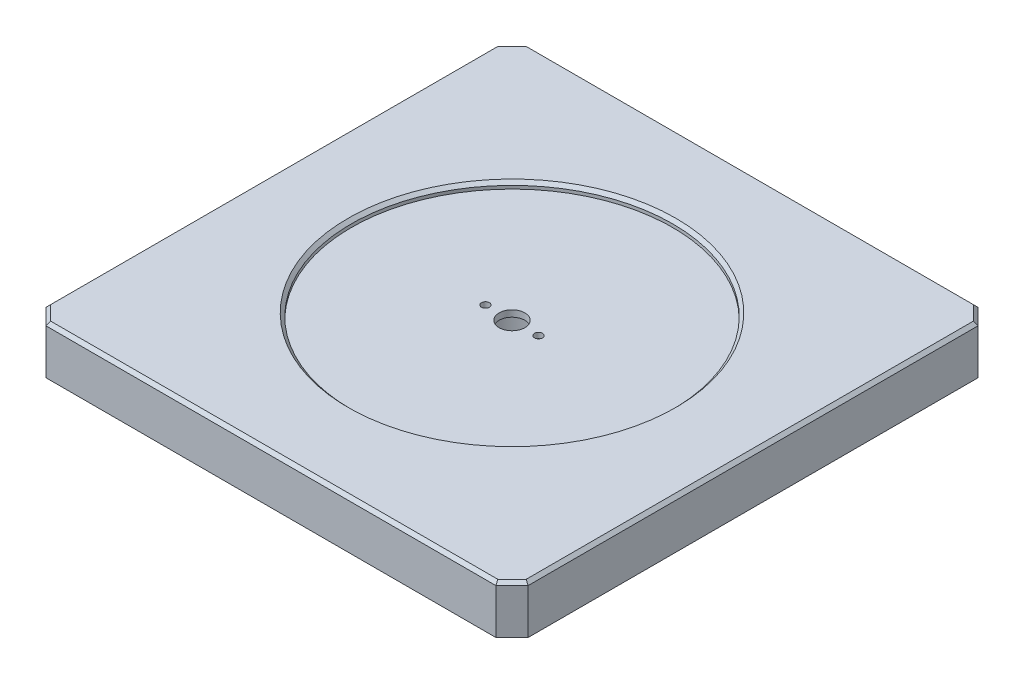
SolidWorks part; units mm, degrees
material "Plain Carbon Steel"
ref_plane "Front Plane" through (0, 0, 0) normal (0, 0, 1) x (1, 0, 0)
ref_plane "Top Plane" through (0, 0, 0) normal (0, 1, 0) x (1, 0, 0)
ref_plane "Right Plane" through (0, 0, 0) normal (1, 0, 0) x (0, 0, -1)
sketch "Sketch1" plane through (0, 0, 0) normal (0, 1, 0) x (1, 0, 0)
  line L1 (75, 75) -> (-75, 75)
  line L2 (75, 75) -> (75, -75)
  line L3 (75, -75) -> (-75, -75)
  line L4 (-75, 75) -> (-75, -75)
  dimension "D1" = 150
  dimension "D2" = 150
  dimension "D3" = 75
  dimension "D4" = 75
extrude "Boss-Extrude1" add sketch "Sketch1" along normal blind 15
sketch "Sketch2" plane through (0, 0, 0) normal (0, -1, 0) x (-1, 0, 0)
  circle A0 centre (0, 0) radius 12.5
  dimension "D1" = 25
extrude "Cut-Extrude1" cut sketch "Sketch2" against normal blind 11 contours A0
sketch "Sketch3" plane through (0, 11, 0) normal (0, -1, 0) x (-1, 0, 0)
  circle A0 centre (0, 0) radius 4
  circle A1 centre (0, 0) radius 12.5 construction
  dimension "D1" = 8
extrude "Cut-Extrude2" cut sketch "Sketch3" against normal through all
sketch "Sketch4" plane through (0, 15, 0) normal (0, 1, 0) x (1, 0, 0)
  circle A0 centre (0, 0) radius 50
  dimension "D1" = 100
extrude "Cut-Extrude3" cut sketch "Sketch4" against normal blind 2
hole_wizard "M3 Tapped Hole1" positions "3DSketch1" profile "Sketch5" tap size "M3" standard "ISO"
sketch3d "3DSketch1"
  line L0 (0, 0, -75) -> (0, 0, 75) construction
  line L1 (75, 0, -75) -> (-75, 0, -75) construction
  line L2 (-75, 0, 75) -> (75, 0, 75) construction
  line L5 (0, 13, 0) -> (0, 11, 0) construction
  line L7 (-12.5, 11, 0) -> (12.5, 11, 0) construction
  circle A0 centre (0, 11, 0) radius 8.25
  circle A1 centre (0, 11, 0) radius 12.5 construction
  point P0 (8.25, 11, 0)
  point P2 (-8.25, 11, 0)
  point P26 (0, 19.25, 0)
  point P42 (0, -1.5, 0)
  dimension "D1" = 16.5
sketch "Sketch5" plane through (8.25, 11, 0) normal (1, 0, 0) x (0, 0, -1)
  line L0 (0, 0) -> (0, 8.2511)
  line L1 (0, 8.2511) -> (1.25, 7.5)
  line L2 (1.25, 7.5) -> (1.25, 0.275)
  line L3 (1.25, 0.275) -> (1.525, 0)
  line L5 (1.525, 0) -> (0, 0)
  line L6 (-1.25, 0.275) -> (-1.525, 0) construction
  line L10 (0, 8.2511) -> (-1.25, 7.5) construction
  line L11 (0, -6.35) -> (0, 107.95) construction
  dimension "Tap Drill Dia." = 2.5
  dimension "Tap Drill Depth" = 7.5
  dimension "Near C'Sink Dia." = 3.05
  dimension "Near C'Sink Angle" = 90
  dimension "Drill Angle" = 118
sketch "Sketch6" plane through (0, 11, 0) normal (0, -1, 0) x (1, 0, 0)
  line L0 (0, -79.8694) -> (0, 75) construction
  line L1 (-75, 75) -> (75, 75) construction
chamfer "Chamfer2" distance 5 angle 45 4 edges at (75, 7.5, -75) (75, 7.5, 75) (-75, 7.5, 75) (-75, 7.5, -75)
chamfer "Chamfer1" distance 1 angle 45 9 edges at (0, 15, 75) (-75, 15, 0) (0, 15, -75) (75, 15, 0) (0, 15, 50) (72.5, 15, 72.5) (-72.5, 15, 72.5) (-72.5, 15, -72.5) (72.5, 15, -72.5)
